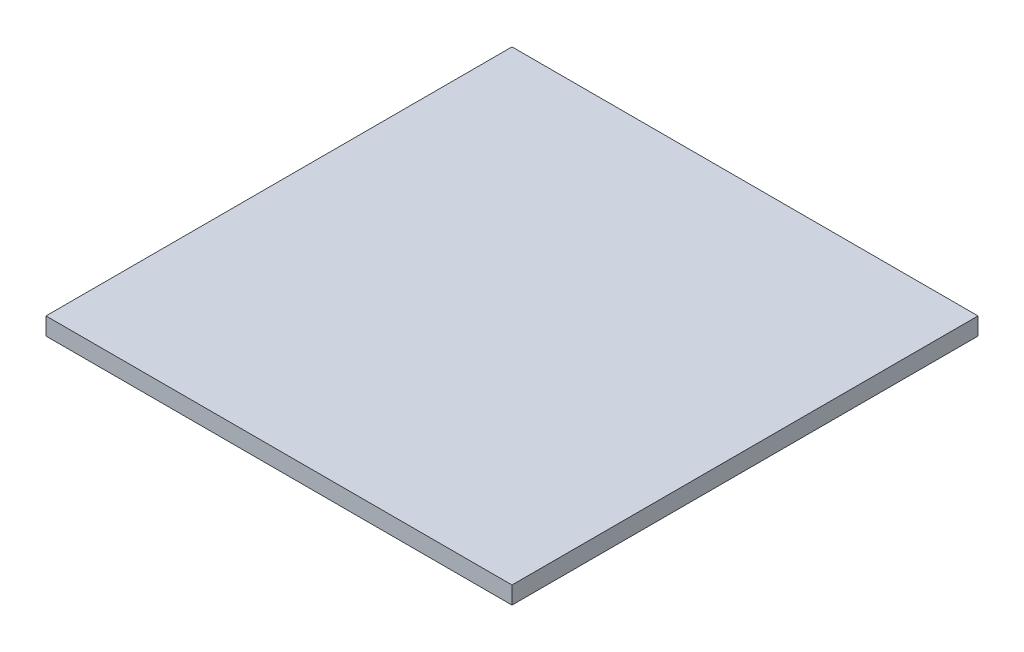
SolidWorks part; units mm, degrees
ref_plane "前视基准面" through (0, 0, 0) normal (0, 0, 1) x (1, 0, 0)
ref_plane "上视基准面" through (0, 0, 0) normal (0, 1, 0) x (1, 0, 0)
ref_plane "右视基准面" through (0, 0, 0) normal (1, 0, 0) x (0, 0, -1)
sketch "草图1" plane through (0, 0, 0) normal (0, 1, 0) x (1, 0, 0)
  line L1 (-40, 40) -> (40, 40)
  line L2 (-40, 40) -> (-40, -40)
  line L3 (-40, -40) -> (40, -40)
  line L4 (40, 40) -> (40, -40)
  point P4 (0, 0)
  point P5 (0, 0)
extrude "凸台-拉伸1" add sketch "草图1" along normal blind 3 contours L2 L1 L4 L3
